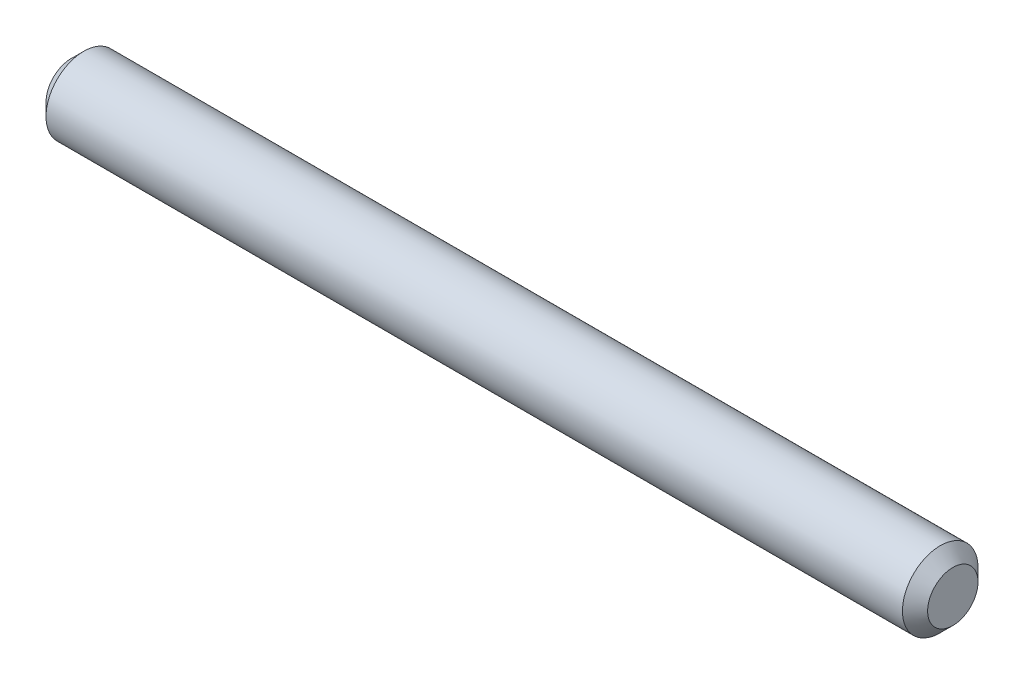
SolidWorks part; units mm, degrees
ref_plane "Piano frontale" through (0, 0, 0) normal (0, 0, 1) x (1, 0, 0)
ref_plane "Piano superiore" through (0, 0, 0) normal (0, 1, 0) x (1, 0, 0)
ref_plane "Piano destro" through (0, 0, 0) normal (1, 0, 0) x (0, 0, -1)
sketch "Schizzo1" plane through (0, 0, 0) normal (1, 0, 0) x (0, 0, -1)
  circle A0 centre (0, 0) radius 3
  dimension "D1" = 6
extrude "Estrusione-Estrusione1" add sketch "Schizzo1" along normal blind 70
chamfer "Smusso1" distance 1 angle 45 2 edges at (0, 0, -3) (70, 0, -3)
